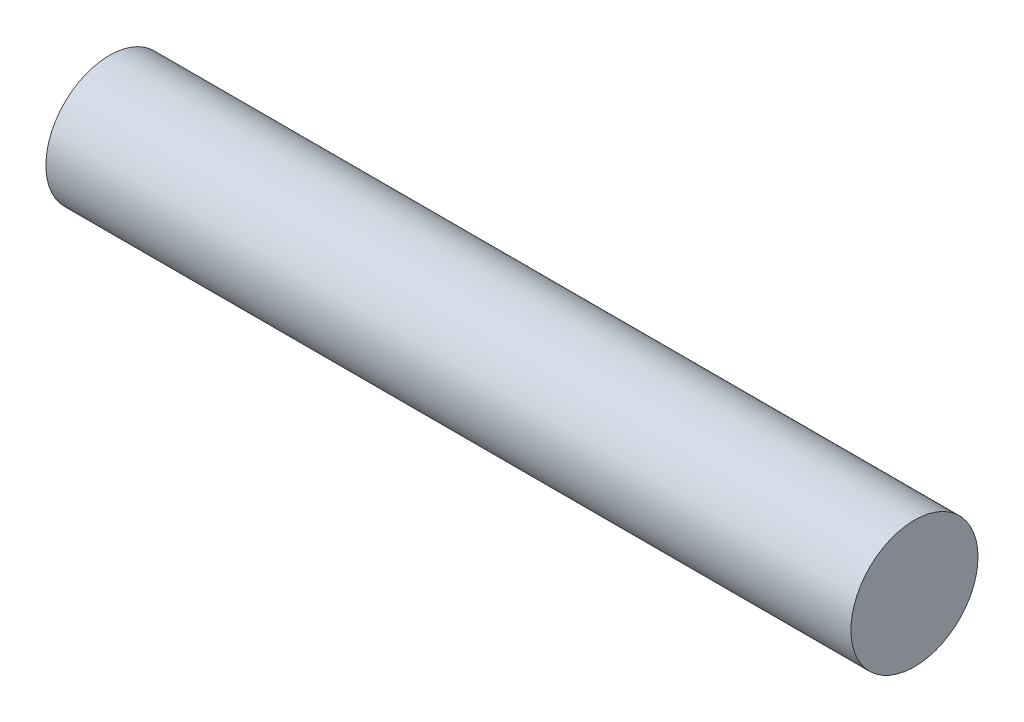
SolidWorks part; units mm, degrees
ref_plane "Front Plane" through (0, 0, 0) normal (0, 0, 1) x (1, 0, 0)
ref_plane "Top Plane" through (0, 0, 0) normal (0, 1, 0) x (1, 0, 0)
ref_plane "Right Plane" through (0, 0, 0) normal (1, 0, 0) x (0, 0, -1)
sketch "Sketch1" plane through (0, 0, 0) normal (1, 0, 0) x (0, 0, -1)
  circle A0 centre (0, 0) radius 3
  dimension "D1" = 6
extrude "Boss-Extrude1" add sketch "Sketch1" along normal mid plane 38
